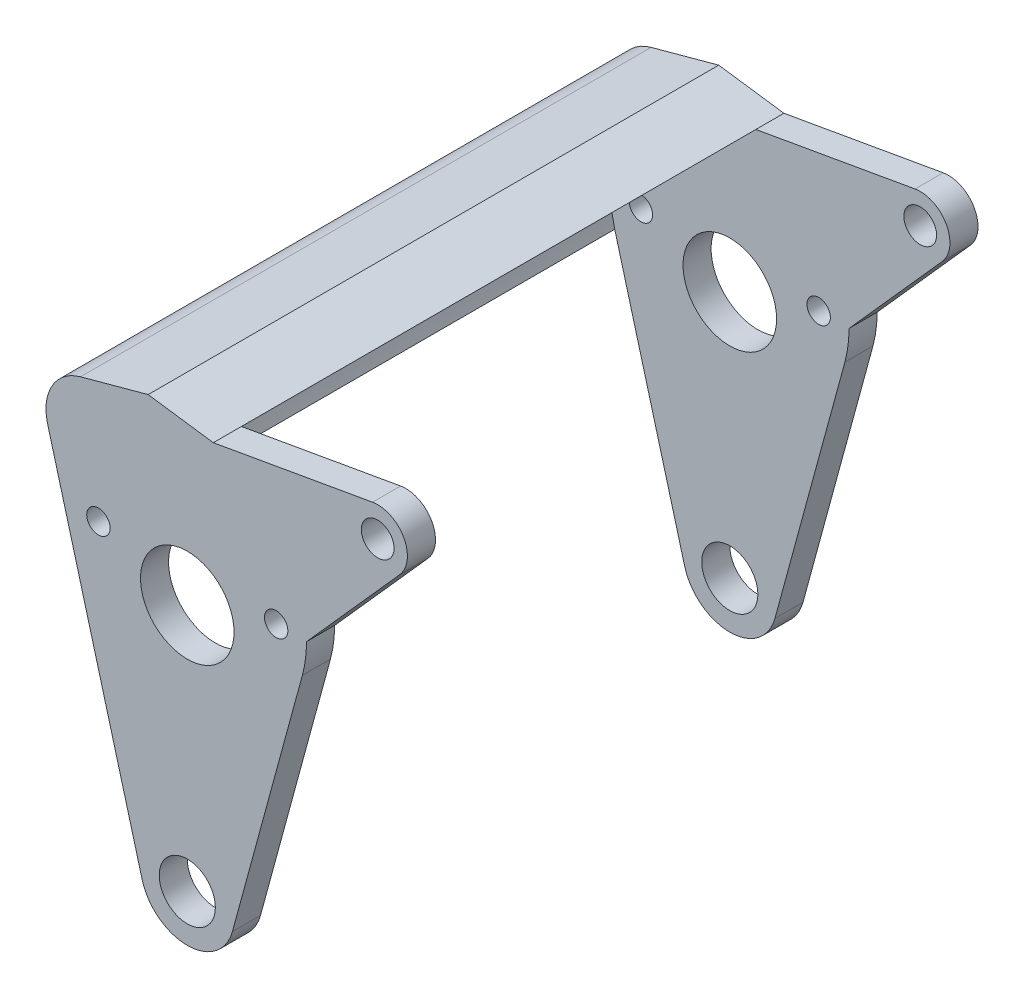
SolidWorks part; units mm, degrees
ref_plane "Front Plane" through (0, 0, 0) normal (0, 0, 1) x (1, 0, 0)
ref_plane "Top Plane" through (0, 0, 0) normal (0, 1, 0) x (1, 0, 0)
ref_plane "Right Plane" through (0, 0, 0) normal (1, 0, 0) x (0, 0, -1)
sketch "Sketch1" plane through (0, 0, 0) normal (0, 0, 1) x (1, 0, 0)
  line L0 (0, 0) -> (0, -29.5) construction
  line L1 (-4.8244, -30.8136) -> (-12.3021, -3.3496)
  line L2 (4.8244, -30.8136) -> (12.3021, -3.3496)
  line L3 (-9.5, 0) -> (9.5, 0) construction
  arc A0 (12.3021, -3.3496) -> (-12.3021, -3.3496) centre (0, 0) ccw
  arc A1 (-4.8244, -30.8136) -> (4.8244, -30.8136) centre (0, -29.5) ccw
  circle A2 centre (0, -29.5) radius 3
  circle A3 centre (0, -3) radius 5
  circle A4 centre (-9.5, 0) radius 1.25
  circle A5 centre (9.5, 0) radius 1.25
  dimension "D1" = 25.5
  dimension "D2" = 10
  dimension "D4" = 6
  dimension "D7" = 10
  dimension "D8" = 2.5
  dimension "D3" = 29.5
  dimension "D5" = 19
  dimension "D6" = 3
extrude "Boss-Extrude1" add sketch "Sketch1" along normal blind 3
sketch "Sketch2" plane through (0, 0, 0) normal (0, 0, 1) x (1, 0, 0)
  line L0 (-2.214, 12.5563) -> (19.8067, 16.4391)
  line L1 (0, 0) -> (12.75, 0) construction
  line L2 (22.7291, 11.199) -> (12.75, 0)
  arc A0 (12.3021, -3.3496) -> (-12.3021, -3.3496) centre (0, 0) ccw construction
  arc A1 (12.75, 0) -> (-2.214, 12.5563) centre (0, 0) ccw
  arc A2 (19.8067, 16.4391) -> (22.7291, 11.199) centre (20.3582, 13.3117) cw
  circle A4 centre (20.3582, 13.3117) radius 1.75
  dimension "D4" = 3.5
  dimension "D1" = 6
  dimension "D2" = 10
  dimension "D3" = 15
extrude "Boss-Extrude2" add sketch "Sketch2" along normal blind 3
sketch "Sketch4" plane through (0, 0, 0) normal (0, 0, 1) x (1, 0, 0)
  line L0 (-12.3021, -3.3496) -> (-14.9293, 6.2992)
  line L1 (-11.4185, 12.4371) -> (-4.1819, 14.4074)
  line L2 (-4.1819, 14.4074) -> (2.786, 13.4379)
  line L3 (19.8067, 16.4391) -> (-2.214, 12.5563) construction
  line L5 (2.786, 13.4379) -> (-2.214, 12.5563)
  line L6 (-12.3021, -3.3496) -> (-4.8244, -30.8136) construction
  arc A0 (-2.214, 12.5563) -> (-12.3021, -3.3496) centre (0, 0) ccw construction
  arc A2 (-2.214, 12.5563) -> (-12.3021, -3.3496) centre (0, 0) ccw
  arc A3 (-14.9293, 6.2992) -> (-11.4185, 12.4371) centre (-10.1049, 7.6127) cw
  point P0 (0, 0)
  point P12 (-13.7848, 18.005)
  point P19 (-16.2428, 11.1235)
  dimension "D1" = 12.5
  dimension "D3" = 5
  dimension "D4" = 5
  dimension "D2" = 15
extrude "Boss-Extrude3" add sketch "Sketch4" along normal blind 30.5
ref_plane "Plane1" through (0, 0, 30.5) normal (0, 0, 1) x (1, 0, 0)
mirror "Mirror2" about plane through (0, 0, 30.5) normal (0, 0, 1) of "Boss-Extrude1", "Boss-Extrude2", "Boss-Extrude3"
